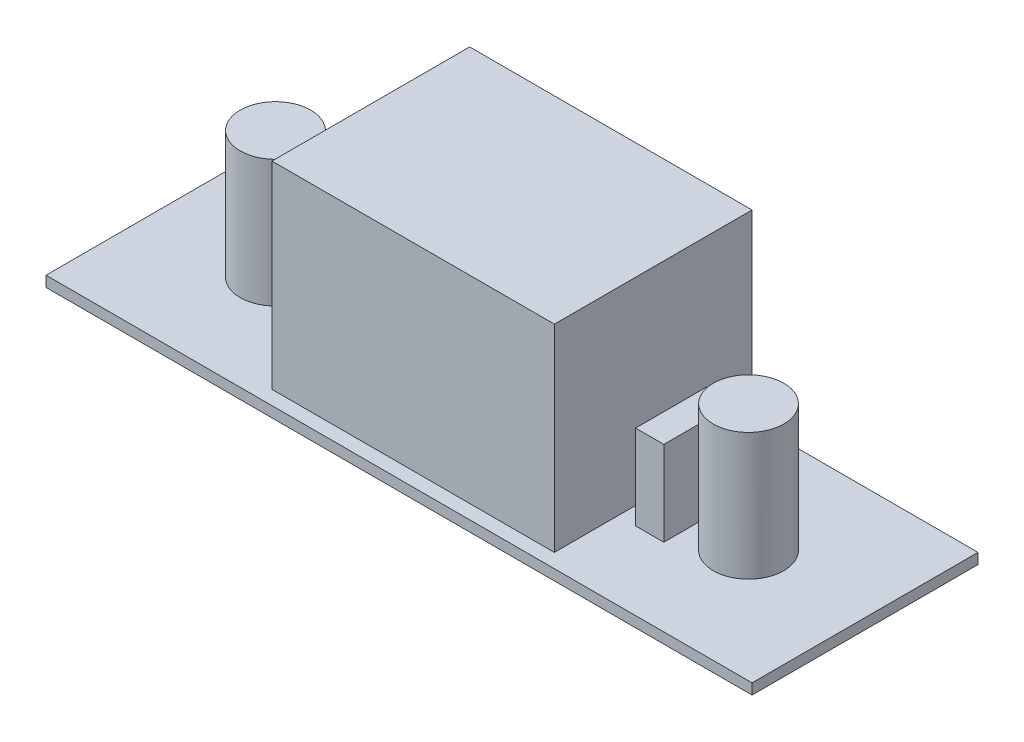
SolidWorks part; units mm, degrees
ref_plane "前视基准面" through (0, 0, 0) normal (0, 0, 1) x (1, 0, 0)
ref_plane "上视基准面" through (0, 0, 0) normal (0, 1, 0) x (1, 0, 0)
ref_plane "右视基准面" through (0, 0, 0) normal (1, 0, 0) x (0, 0, -1)
sketch "草图1" plane through (0, 0, 0) normal (0, 1, 0) x (1, 0, 0)
  line L1 (0, 0) -> (100, 0)
  line L2 (0, 0) -> (0, 32)
  line L3 (0, 32) -> (100, 32)
  line L4 (100, 0) -> (100, 32)
  dimension "D1" = 32
  dimension "D2" = 100
extrude "凸台-拉伸1" add sketch "草图1" along normal blind 1.5
sketch "草图2" plane through (0, 1.5, 0) normal (0, 1, 0) x (1, 0, 0)
  line L1 (30, 2.0008) -> (70, 2.0008)
  line L2 (30, 2.0008) -> (30, 30.0008)
  line L3 (30, 30.0008) -> (70, 30.0008)
  line L4 (70, 2.0008) -> (70, 30.0008)
  dimension "D1" = 40
  dimension "D2" = 28
  dimension "D3" = 30
  dimension "D4" = 2.0008
extrude "凸台-拉伸2" add sketch "草图2" along normal blind 28
sketch "草图3" plane through (0, 1.5, 0) normal (0, 1, 0) x (1, 0, 0)
  line L0 (0, 32) -> (0, 0) construction
  line L1 (100, 0) -> (100, 32) construction
  circle A0 centre (16.5, 16) radius 5
  circle A1 centre (83.5, 16) radius 5
  dimension "D1" = 10
  dimension "D2" = 10
  dimension "D3" = 16
  dimension "D4" = 16.5
  dimension "D5" = 16.5
extrude "凸台-拉伸3" add sketch "草图3" along normal blind 18
sketch "草图4" plane through (0, 1.5, 0) normal (0, 1, 0) x (1, 0, 0)
  line L0 (0, 0) -> (100, 0) construction
  line L1 (72.5, 21) -> (76.5, 21)
  line L2 (72.5, 21) -> (72.5, 11)
  line L3 (72.5, 11) -> (76.5, 11)
  line L4 (76.5, 21) -> (76.5, 11)
  dimension "D1" = 10
  dimension "D2" = 4
  dimension "D3" = 72.5
  dimension "D4" = 11
extrude "凸台-拉伸4" add sketch "草图4" along normal blind 12
